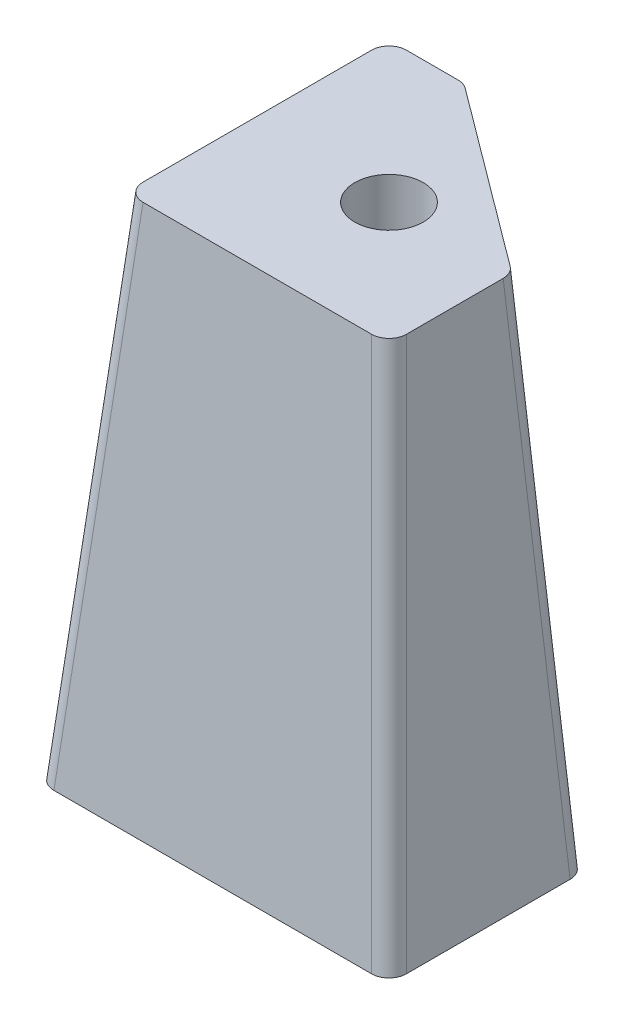
SolidWorks part; units mm, degrees
ref_plane "Front Plane" through (0, 0, 0) normal (0, 0, 1) x (1, 0, 0)
ref_plane "Top Plane" through (0, 0, 0) normal (0, 1, 0) x (1, 0, 0)
ref_plane "Right Plane" through (0, 0, 0) normal (1, 0, 0) x (0, 0, -1)
sketch "Sketch1" plane through (0, 0, 0) normal (0, 1, 0) x (1, 0, 0)
  line L3 (10.4204, -7.2013) -> (-4.5796, -7.2013)
  line L5 (-4.5796, -7.2013) -> (-4.5796, 7.7987)
  line L6 (-4.5796, 7.7987) -> (-0.3125, 7.7987)
  line L7 (-0.3125, 7.7987) -> (10.4204, -0.2013)
  line L8 (10.4204, -0.2013) -> (10.4204, -7.2013)
  dimension "D1" = 15
  dimension "D2" = 15
  dimension "D3" = 7
  dimension "D4" = 126.7
extrude "Boss-Extrude1" add sketch "Sketch1" along normal blind 29
sketch "Sketch2" plane through (0, 0, 0) normal (0, -1, 0) x (1, 0, 0)
  line L1 (10.4204, 7.2013) -> (10.4204, 0.2013) construction
  line L2 (-4.5796, 7.2013) -> (10.4204, 7.2013) construction
  line L3 (-4.5796, -7.7987) -> (-4.5796, 7.2013) construction
  circle A0 centre (-0.5796, 2.2013) radius 2
  circle A1 centre (7.4204, 2.2013) radius 1.5
  dimension "D1" = 4
  dimension "D3" = 3
  dimension "D2" = 4
  dimension "D4" = 3
  dimension "D5" = 5
  dimension "D6" = 5
extrude "Cut-Extrude1" cut sketch "Sketch2" against normal blind 10
sketch "Sketch3" plane through (0, 29, 0) normal (0, 1, 0) x (1, 0, 0)
  line L0 (10.4204, -7.2013) -> (10.4204, -0.2013) construction
  line L1 (-4.5796, -7.2013) -> (10.4204, -7.2013) construction
  circle A0 centre (3.4204, -0.2013) radius 1.95
  dimension "D1" = 3.9
  dimension "D2" = 7
  dimension "D3" = 7
extrude "Cut-Extrude2" cut sketch "Sketch3" against normal blind 6
draft "Draft1" type of draft neutral plane draft angle 5 faces to draft 5 face at (5.0539, 14.5, -3.7987) face at (-2.4461, 14.5, -7.7987) face at (-4.5796, 14.5, -0.2987) face at (10.4204, 14.5, 3.7013) face at (2.9204, 14.5, 7.2013) neutral plane through (0, 29, 0) neutral plane normal (0, 1, 0) parameters "D1"=5
fillet "Fillet1" radius 1 5 edges at (-5.8482, 14.5, 8.4699) (11.6889, 14.5, 8.4699) (-5.8482, 14.5, -9.0673) (0.1083, 14.5, -9.0673) (11.6889, 14.5, -0.4353)
